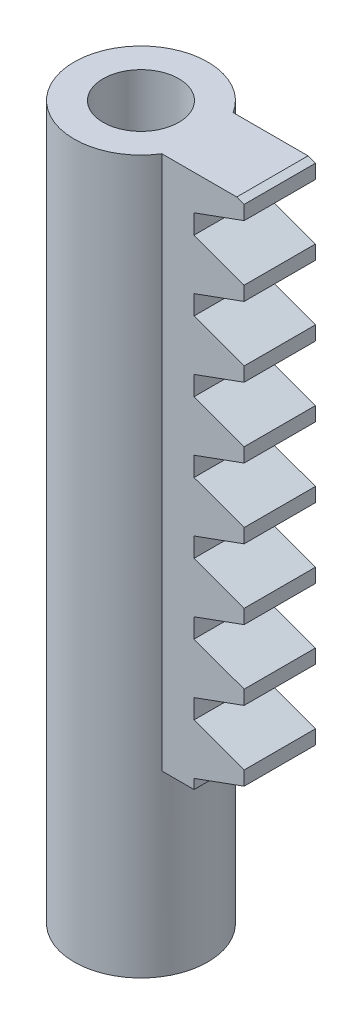
SolidWorks part; units mm, degrees
ref_plane "Alzado" through (0, 0, 0) normal (0, 0, 1) x (1, 0, 0)
ref_plane "Planta" through (0, 0, 0) normal (0, 1, 0) x (1, 0, 0)
ref_plane "Vista lateral" through (0, 0, 0) normal (1, 0, 0) x (0, 0, -1)
ref_plane "Plano1" through (0, 0, 0) normal (0, 0, -1) x (-1, 0, 0)
sketch "Croquis1" plane through (0, 0, 0) normal (0, 0, -1) x (-1, 0, 0)
  line L0 (-5.5474, 27.6157) -> (-5.5474, 26.0306)
  line L1 (-5.5474, 26.0306) -> (0.0776, 23.9833)
  line L2 (0.0776, 23.9833) -> (0.0776, 21.8091)
  line L3 (0.0776, 21.8091) -> (-5.5474, 19.7618)
  line L4 (-5.5474, 19.7618) -> (-5.5474, 18.1766)
  line L5 (-5.5474, 18.1766) -> (0.0776, 16.1293)
  line L6 (0.0776, 16.1293) -> (0.0776, 13.9551)
  line L7 (0.0776, 13.9551) -> (-5.5474, 11.9078)
  line L8 (-5.5474, 11.9078) -> (-5.5474, 10.3226)
  line L9 (-5.5474, 10.3226) -> (0.0776, 8.2753)
  line L10 (0.0776, 8.2753) -> (0.0776, 6.1011)
  line L11 (0.0776, 6.1011) -> (-5.5474, 4.0538)
  line L12 (-5.5474, 4.0538) -> (-5.5474, 2.4687)
  line L13 (-5.5474, 2.4687) -> (0.0776, 0.4213)
  line L14 (0.0776, 0.4213) -> (0.0776, -1.7528)
  line L15 (0.0776, -1.7528) -> (-5.5474, -3.8002)
  line L16 (-5.5474, -3.8002) -> (-5.5474, -5.3853)
  line L17 (-5.5474, -5.3853) -> (0.0776, -7.4327)
  line L18 (0.0776, -7.4327) -> (0.0776, -9.6068)
  line L19 (0.0776, -9.6068) -> (-5.5474, -11.6542)
  line L20 (-5.5474, -11.6542) -> (-5.5474, -13.2393)
  line L21 (-5.5474, -13.2393) -> (0.0776, -15.2866)
  line L22 (0.0776, -15.2866) -> (0.0776, -17.4608)
  line L23 (0.0776, -17.4608) -> (-5.5474, -19.5081)
  line L24 (-5.5474, -19.5081) -> (-5.5474, -21.0933)
  line L25 (-5.5474, -21.0933) -> (0.0776, -23.1406)
  line L26 (0.0776, -23.1406) -> (0.0776, -25.3148)
  line L27 (0.0776, -25.3148) -> (-5.5474, -27.3621)
  line L28 (-5.5474, -27.3621) -> (-5.5474, -28.9473)
  line L29 (-5.5474, -28.9473) -> (0.0776, -30.9946)
  line L30 (0.0776, -30.9946) -> (0.0776, -32.0817)
  line L31 (0.0776, -32.0817) -> (4.9526, -32.0817)
  line L32 (4.9526, -32.0817) -> (4.9526, 27.9183)
  line L33 (4.9526, 27.9183) -> (-4.7161, 27.9183)
  line L34 (-4.7161, 27.9183) -> (-5.5474, 27.6157)
extrude "Saliente-Extruir1" add sketch "Croquis1" against normal blind 8
sketch "Croquis2" plane through (0, 27.9183, 0) normal (0, 1, 0) x (1, 0, 0)
  line L0 (-4.9526, -4) -> (4.7161, -4) construction
  line L1 (-4.9526, -8) -> (-4.9526, 0) construction
  line L2 (4.7161, -8) -> (4.7161, 0) construction
  line L3 (0, 0) -> (-0.0776, -8) construction
  line L4 (-4.9526, -4) -> (-0.1183, -4)
  circle A0 centre (-10.0354, -4) radius 7.5
  circle A1 centre (-10.0354, -4) radius 4.25
  point P13 (-2.5354, -4)
  line M6 (4.7161, 0) -> (-4.9526, 0)
  line M7 (-4.9526, 0) -> (-4.9526, -8)
  line M8 (-4.9526, -8) -> (4.7161, -8)
  dimension "D4" = 15
  dimension "D5" = 8.5
  dimension "D1" = 9.6687
  dimension "D2" = 8
  dimension "D3" = 4.8344
extrude "Saliente-Extruir2" add sketch "Croquis2" against normal blind 80 contours A0 A1 M6 M8 M7
ref_plane "Plano2" through (-17.5354, 0, 0) normal (-1, 0, 0) x (0, 0, 1)
sketch "Croquis4" plane through (-17.5354, 0, 0) normal (-1, 0, 0) x (0, 0, 1)
  line L0 (4, 27.9183) -> (4, -52.0817) construction
  line L1 (11.5, 27.9183) -> (-3.5, 27.9183) construction
  line L2 (-3.5, -52.0817) -> (11.5, -52.0817) construction
  line L3 (4, 27.9183) -> (4, 12.9183)
  line L4 (4, -52.0817) -> (4, -37.0817)
  circle A0 centre (4, 12.9183) radius 1.5
  circle A1 centre (4, -37.0817) radius 1.5
  circle A2 centre (4, -12.0817) radius 1.5
  dimension "D3" = 3
  dimension "D4" = 3
  dimension "D1" = 15
  dimension "D2" = 15
extrude "Cortar-Extruir1" cut sketch "Croquis4" against normal blind 5 contours A0 | A1
sketch "Croquis5" plane through (-17.5354, 0, 0) normal (-1, 0, 0) x (0, 0, 1)
  line L0 (4, 12.9183) -> (4, -37.0817) construction
  circle A0 centre (4, -12.0817) radius 1.5
  dimension "D1" = 3
extrude "Cortar-Extruir2" cut sketch "Croquis5" along normal mid plane 14
sketch "Croquis6" plane through (0, -52.0817, 0) normal (0, -1, 0) x (1, 0, 0)
  circle A0 centre (-10.0354, 4) radius 4.25
  circle A1 centre (-10.0354, 4) radius 7.5
  dimension "D1" = 15
  dimension "D2" = 8.5
extrude "Saliente-Extruir3" add sketch "Croquis6" against normal blind 70
sketch "Croquis7" plane through (-17.5354, 0, 0) normal (-1, 0, 0) x (0, 0, 1)
  circle A0 centre (4, -12.0817) radius 1.5
  circle A1 centre (4, -37.0817) radius 1.5
  circle A2 centre (4, 12.9183) radius 1.5
  dimension "D1" = 3
  dimension "D2" = 3
  dimension "D3" = 3
extrude "Cortar-Extruir3" cut sketch "Croquis7" against normal blind 10
sketch "Croquis11" plane through (-17.5354, 0, 0) normal (-1, 0, 0) x (0, 0, 1)
  circle A0 centre (4, 12.9183) radius 2.5
  circle A1 centre (4, -12.0817) radius 2.5
  circle A2 centre (4, -37.0817) radius 2.5
  dimension "D1" = 5
  dimension "D2" = 5
  dimension "D3" = 5
extrude "Cortar-Extruir4" cut sketch "Croquis11" against normal blind 1.8
